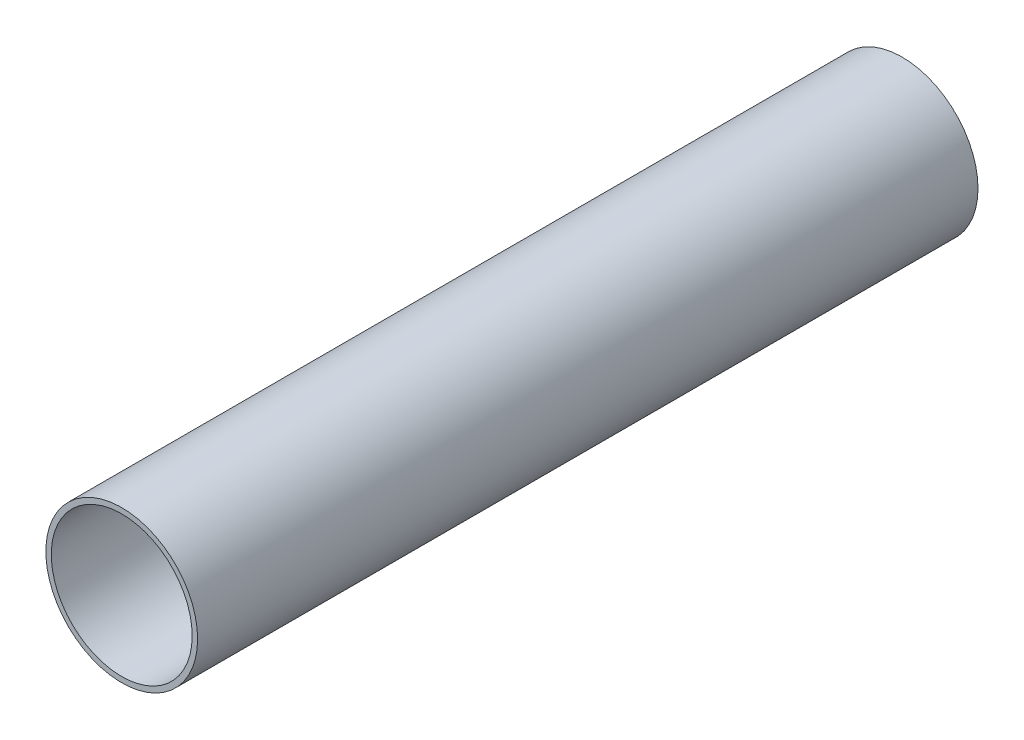
SolidWorks part; units mm, degrees
material "Acrylic (Medium-high impact)"
ref_plane "Front Plane" through (0, 0, 0) normal (0, 0, 1) x (1, 0, 0)
ref_plane "Top Plane" through (0, 0, 0) normal (0, 1, 0) x (1, 0, 0)
ref_plane "Right Plane" through (0, 0, 0) normal (1, 0, 0) x (0, 0, -1)
sketch "Sketch1" plane through (0, 0, 0) normal (0, 0, 1) x (1, 0, 0)
  circle A0 centre (0, 0) radius 88.9
  circle A1 centre (0, 0) radius 82.55
  dimension "D1" = 177.8
  dimension "D2" = 165.1
extrude "Boss-Extrude1" add sketch "Sketch1" along normal blind 914.4
